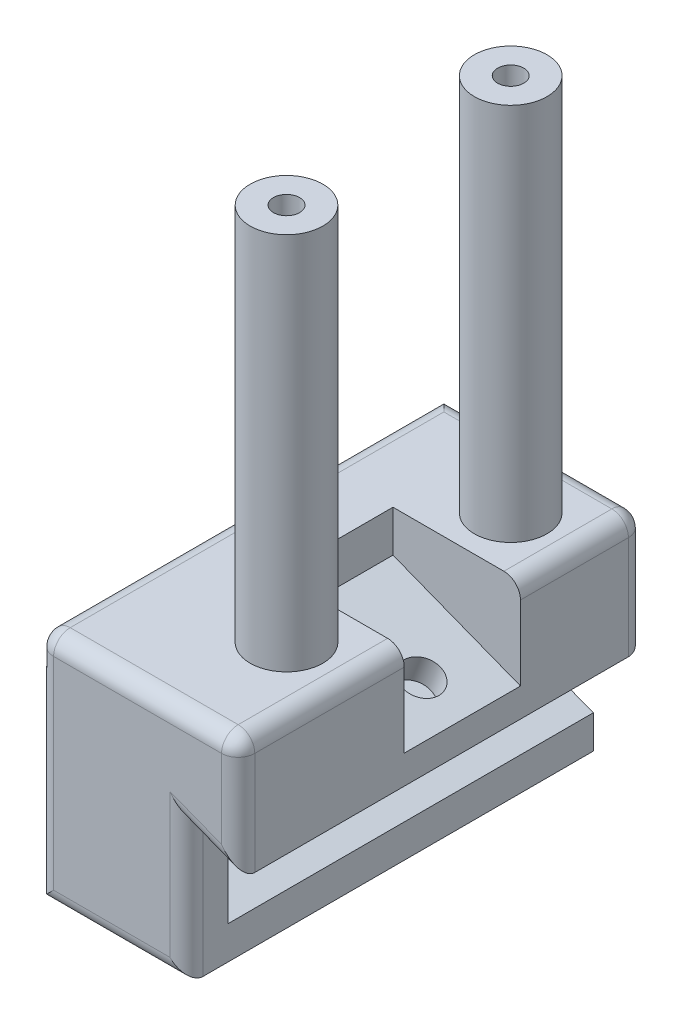
SolidWorks part; units mm, degrees
other "Markup1"
sketch "Sketch10" plane through (30.7748, 80.4925, 62.23) normal (0.2074, 0.1155, 0.9714) x (0.96, 0.1671, -0.2249)
ref_plane "Front Plane" through (0, 0, 0) normal (0, 0, 1) x (1, 0, 0)
ref_plane "Top Plane" through (0, 0, 0) normal (0, 1, 0) x (1, 0, 0)
ref_plane "Right Plane" through (0, 0, 0) normal (1, 0, 0) x (0, 0, -1)
sketch "Sketch1" plane through (0, 0, 0) normal (0, 0, 1) x (1, 0, 0)
  line L0 (0, 0) -> (22.86, 0)
  line L1 (22.86, 0) -> (22.86, 5.08)
  line L2 (22.86, 5.08) -> (0, 13.97)
  line L3 (0, 13.97) -> (0, 0)
  dimension "D1" = 22.86
  dimension "D2" = 13.97
  dimension "D3" = 5.08
extrude "Boss-Extrude1" add sketch "Sketch1" along normal blind 55.88
sketch "Sketch2" plane through (0, 0, 55.88) normal (0, 0, 1) x (1, 0, 0)
  line L0 (0, 0) -> (0, 29.6925)
  line L1 (0, 29.6925) -> (22.86, 29.6925)
  line L2 (22.86, 29.6925) -> (22.86, 0)
  line L3 (0, 0) -> (22.86, 0) construction
  line L4 (22.86, 0) -> (0, 0)
extrude "Boss-Extrude2" add sketch "Sketch2" along normal blind 6.35
sketch "Sketch3" plane through (0, 0, 55.88) normal (0, 0, -1) x (-1, 0, 0)
  line L0 (-22.86, 29.6925) -> (0, 29.6925)
  line L1 (-22.86, 29.6925) -> (0, 29.6925) construction
  line L2 (0, 29.6925) -> (-30.7748, 17.7245)
  line L4 (-30.7748, 17.7245) -> (-30.7748, 29.6925)
  line L5 (-22.86, 5.08) -> (0, 13.97) construction
  line L7 (-30.7748, 29.6925) -> (-22.86, 29.6925)
  dimension "D1" = 33.02
extrude "Boss-Extrude3" add sketch "Sketch3" along normal blind 55.88 contours L7 L0 L2 L4
sketch "Sketch5" plane through (0, 0, 0) normal (0, 0, -1) x (-1, 0, 0)
  line L0 (-30.7748, 22.1078) -> (-11.2714, 29.6925)
  line L1 (-30.7748, 17.7245) -> (-30.7748, 29.6925) construction
  line L3 (0, 29.6925) -> (-22.86, 20.8025) construction
  line L4 (-30.7748, 29.6925) -> (0, 29.6925) construction
  line L5 (-11.2714, 29.6925) -> (-30.7748, 29.6925)
  line L6 (-30.7748, 29.6925) -> (-30.7748, 22.1078)
extrude "Cut-Extrude1" cut sketch "Sketch5" against normal blind 55.88
sketch "Sketch6" plane through (0, 0, 0) normal (0, 0, -1) x (-1, 0, 0)
  line L0 (-11.2714, 29.6925) -> (-30.7748, 29.6925)
  line L1 (-30.7748, 29.6925) -> (-30.7748, 22.1078)
  line L2 (-30.7748, 22.1078) -> (-11.2714, 29.6925)
extrude "Boss-Extrude5" add sketch "Sketch6" against normal blind 19.05 separate body contours L1 L2 L0
sketch "Sketch7" plane through (0, 0, 55.88) normal (0, 0, 1) x (1, 0, 0)
  line L0 (30.7748, 22.1078) -> (30.7748, 29.6925)
  line L1 (30.7748, 29.6925) -> (11.2714, 29.6925)
  line L2 (11.2714, 29.6925) -> (30.7748, 22.1078)
extrude "Boss-Extrude6" add sketch "Sketch7" against normal blind 19.05
sketch "Sketch8" plane through (11.5109, 29.5994, 0) normal (0.3624, 0.932, 0) x (0.932, -0.3624, 0)
  line L1 (-10.7619, 0) -> (-10.7619, -55.88) construction
  line L2 (-10.7619, -27.94) -> (20.6693, -27.94) construction
  line L3 (20.6693, -36.83) -> (20.6693, 0) construction
  circle A0 centre (13.9633, -27.94) radius 2.8575
  dimension "D1" = 5.715
  dimension "D2" = 0
extrude "Cut-Extrude2" cut sketch "Sketch8" against normal up to next (4.0853 mm away)
sketch "Sketch9" plane through (0, 29.6925, 0) normal (0, 1, 0) x (1, 0, 0)
  line L0 (21.0231, -36.83) -> (21.0231, -62.23) construction
  line L1 (11.2714, -36.83) -> (30.7748, -36.83) construction
  line L2 (22.86, -62.23) -> (0, -62.23) construction
  line L5 (0, 0) -> (0, -55.88) construction
  line L7 (21.0231, -19.05) -> (21.0231, 0) construction
  line L8 (11.2714, -19.05) -> (30.7748, -19.05) construction
  line L9 (11.2714, 0) -> (30.7748, 0) construction
  line L10 (0, -27.94) -> (36.4511, -27.94) construction
  circle A0 centre (21.0231, -10.795) radius 5.5562
  circle A1 centre (21.0231, -45.085) radius 5.5563
  dimension "D1" = 11.1125
  dimension "D2" = 11.1125
  dimension "D3" = 17.145
  dimension "D4" = 17.145
extrude "Boss-Extrude7" add sketch "Sketch9" along normal blind 64.262
sketch "Sketch11" plane through (0, 93.9545, 0) normal (0, 1, 0) x (1, 0, 0)
  circle A0 centre (21.0231, -10.795) radius 2
  circle A1 centre (21.0231, -45.085) radius 2
  dimension "D1" = 4
  dimension "D2" = 4
extrude "Cut-Extrude3" cut sketch "Sketch11" against normal blind 7
sketch "Sketch12" plane through (0, 0, 55.88) normal (0, 0, 1) x (1, 0, 0)
  line L0 (22.86, 29.6925) -> (30.7748, 29.6925)
  line L1 (30.7748, 29.6925) -> (30.7748, 17.7245)
  line L2 (30.7748, 17.7245) -> (22.86, 20.8025)
  line L3 (22.86, 20.8025) -> (22.86, 29.6925)
extrude "Boss-Extrude8" add sketch "Sketch12" along normal up to surface (6.35 mm away) up to face at (11.43, 14.8462, 62.23)
sketch "Sketch14" plane through (0, 29.6925, 0) normal (0, 1, 0) x (1, 0, 0)
  line L0 (0, 0) -> (0, -62.23)
  line L1 (0, -62.23) -> (30.7748, -62.23)
  line L2 (30.7748, -62.23) -> (30.7748, -36.83)
  line L3 (30.7748, -36.83) -> (11.2714, -36.83)
  line L4 (11.2714, -36.83) -> (11.2714, -19.05)
  line L5 (11.2714, -19.05) -> (30.7748, -19.05)
  line L6 (30.7748, -19.05) -> (30.7748, 0)
  line L7 (30.7748, 0) -> (0, 0)
extrude "Boss-Extrude9" add sketch "Sketch14" along normal blind 6.35
fillet "Fillet3" radius 2.54 12 edges at (0, 18.0212, 62.23) (15.3874, 36.0425, 62.23) (30.7748, 26.8835, 0) (30.7748, 26.8835, 62.23) (26.8174, 19.2635, 62.23) (22.86, 10.4012, 62.23) (11.43, 0, 62.23) (0, 6.985, 0) (15.3874, 36.0425, 0) (0, 36.0425, 31.115) (30.7748, 36.0425, 49.53) (30.7748, 36.0425, 9.525)
